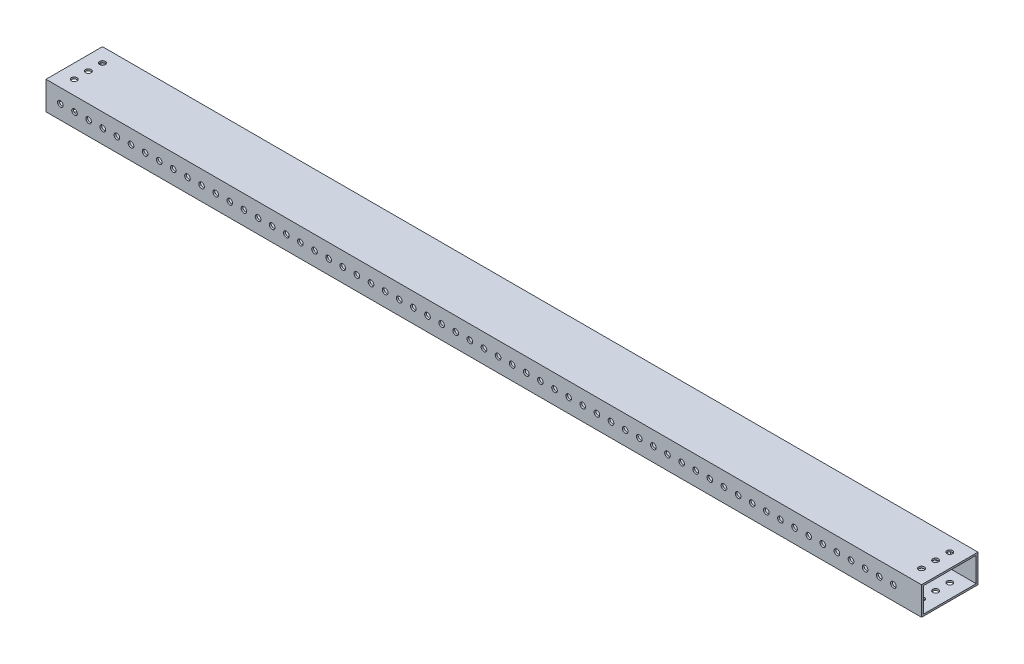
SolidWorks part; units mm, degrees
ref_plane "Front Plane" through (0, 0, 0) normal (0, 0, 1) x (1, 0, 0)
ref_plane "Top Plane" through (0, 0, 0) normal (0, 1, 0) x (1, 0, 0)
ref_plane "Right Plane" through (0, 0, 0) normal (1, 0, 0) x (0, 0, -1)
sketch "Sketch1" plane through (0, 0, 0) normal (0, 1, 0) x (1, 0, 0)
  line L1 (393.7901, 25.4) -> (-393.7901, 25.4)
  line L2 (393.7901, 25.4) -> (393.7901, -25.4)
  line L3 (393.7901, -25.4) -> (-393.7901, -25.4)
  line L4 (-393.7901, 25.4) -> (-393.7901, -25.4)
  line L5 (393.7901, 25.4) -> (-393.7901, -25.4) construction
  line L6 (393.7901, -25.4) -> (-393.7901, 25.4) construction
  point P0 (0, 0)
  dimension "D1" = 50.8
extrude "Boss-Extrude1" add sketch "Sketch1" along normal blind 25.4
sketch "Sketch2" plane through (-393.7901, 0, 0) normal (-1, 0, 0) x (0, 0, 1)
  line L1 (23.7937, 23.7836) -> (-23.7836, 23.7836)
  line L2 (23.7937, 23.7836) -> (23.7937, 1.6265)
  line L3 (23.7937, 1.6265) -> (-23.7836, 1.6265)
  line L4 (-23.7836, 23.7836) -> (-23.7836, 1.6265)
  line L6 (-25.4, 25.4) -> (-25.4, 0) construction
  line L7 (25.4, 25.4) -> (25.4, 0) construction
  dimension "D1" = 2.286
  dimension "D2" = 2.286
  dimension "D3" = 1.6164
  dimension "D4" = 1.6063
extrude "Cut-Extrude1" cut sketch "Sketch2" against normal through all
sketch "Sketch3" plane through (0, 0, 25.4) normal (0, 0, 1) x (1, 0, 0)
  line L0 (-1393.7901, 12.7) -> (48606.2099, 12.7) construction
  line L1 (-393.7901, 25.4) -> (-393.7901, 0) construction
  circle A1 centre (-380.8361, 12.7) radius 2.54
  circle A2 centre (-368.1361, 12.7) radius 2.54
  circle A3 centre (-355.4361, 12.7) radius 2.54
  circle A4 centre (-342.7361, 12.7) radius 2.54
  circle A5 centre (-330.0361, 12.7) radius 2.54
  circle A6 centre (-317.3361, 12.7) radius 2.54
  circle A7 centre (-304.6361, 12.7) radius 2.54
  circle A8 centre (-291.9361, 12.7) radius 2.54
  circle A9 centre (-279.2361, 12.7) radius 2.54
  circle A10 centre (-266.5361, 12.7) radius 2.54
  circle A11 centre (-253.8361, 12.7) radius 2.54
  circle A12 centre (-241.1361, 12.7) radius 2.54
  circle A13 centre (-228.4361, 12.7) radius 2.54
  circle A14 centre (-215.7361, 12.7) radius 2.54
  circle A15 centre (-203.0361, 12.7) radius 2.54
  circle A16 centre (-190.3361, 12.7) radius 2.54
  circle A17 centre (-177.6361, 12.7) radius 2.54
  circle A18 centre (-164.9361, 12.7) radius 2.54
  circle A19 centre (-152.2361, 12.7) radius 2.54
  circle A20 centre (-139.5361, 12.7) radius 2.54
  circle A21 centre (-126.8361, 12.7) radius 2.54
  circle A22 centre (-114.1361, 12.7) radius 2.54
  circle A23 centre (-101.4361, 12.7) radius 2.54
  circle A24 centre (-88.7361, 12.7) radius 2.54
  circle A25 centre (-76.0361, 12.7) radius 2.54
  circle A26 centre (-63.3361, 12.7) radius 2.54
  circle A27 centre (-50.6361, 12.7) radius 2.54
  circle A28 centre (-37.9361, 12.7) radius 2.54
  circle A29 centre (-25.2361, 12.7) radius 2.54
  circle A30 centre (-12.5361, 12.7) radius 2.54
  circle A31 centre (0.1639, 12.7) radius 2.54
  circle A32 centre (12.8639, 12.7) radius 2.54
  circle A33 centre (25.5639, 12.7) radius 2.54
  circle A34 centre (38.2639, 12.7) radius 2.54
  circle A35 centre (50.9639, 12.7) radius 2.54
  circle A36 centre (63.6639, 12.7) radius 2.54
  circle A37 centre (76.3639, 12.7) radius 2.54
  circle A38 centre (89.0639, 12.7) radius 2.54
  circle A39 centre (101.7639, 12.7) radius 2.54
  circle A40 centre (114.4639, 12.7) radius 2.54
  circle A41 centre (127.1639, 12.7) radius 2.54
  circle A42 centre (139.8639, 12.7) radius 2.54
  circle A43 centre (152.5639, 12.7) radius 2.54
  circle A44 centre (165.2639, 12.7) radius 2.54
  circle A45 centre (177.9639, 12.7) radius 2.54
  circle A46 centre (190.6639, 12.7) radius 2.54
  circle A47 centre (203.3639, 12.7) radius 2.54
  circle A48 centre (216.0639, 12.7) radius 2.54
  circle A49 centre (228.7639, 12.7) radius 2.54
  circle A50 centre (241.4639, 12.7) radius 2.54
  circle A51 centre (254.1639, 12.7) radius 2.54
  circle A52 centre (266.8639, 12.7) radius 2.54
  circle A53 centre (279.5639, 12.7) radius 2.54
  circle A54 centre (292.2639, 12.7) radius 2.54
  circle A55 centre (304.9639, 12.7) radius 2.54
  circle A56 centre (317.6639, 12.7) radius 2.54
  circle A57 centre (330.3639, 12.7) radius 2.54
  circle A58 centre (343.0639, 12.7) radius 2.54
  circle A59 centre (355.7639, 12.7) radius 2.54
  circle A60 centre (368.4639, 12.7) radius 2.54
  point P5 (-393.7901, 12.7)
  dimension "D1" = 5.08
  dimension "D2" = 12.954
  dimension "D4" = 12.7
  dimension "D3" = 60
extrude "Cut-Extrude2" cut sketch "Sketch3" against normal through all
sketch "Sketch4" plane through (0, 25.4, 0) normal (0, 1, 0) x (1, 0, 0)
  line L0 (-1393.7901, 0) -> (48606.2099, 0) construction
  line L1 (-393.7901, 25.4) -> (-393.7901, -25.4) construction
  line L2 (-1388.247, 12.7) -> (48611.753, 12.7) construction
  line L3 (-1379.4121, -12.7) -> (48620.5879, -12.7) construction
  line L4 (-393.7901, -25.4) -> (393.7901, -25.4) construction
  line L5 (0, 25.4) -> (0, -25.4) construction
  line L6 (393.7901, 25.4) -> (-393.7901, 25.4) construction
  circle A0 centre (-381.0901, 12.7) radius 2.54
  circle A2 centre (-381.0901, -12.7) radius 2.54
  circle A3 centre (-381.0901, 0) radius 2.54
  circle A4 centre (381.0901, 12.7) radius 2.54
  circle A5 centre (381.0901, 0) radius 2.54
  circle A6 centre (381.0901, -12.7) radius 2.54
  point P5 (-393.7901, 0)
  dimension "D1" = 5.08
  dimension "D5" = 12.7
  dimension "D6" = 5.08
  dimension "D2" = 12.7
  dimension "D3" = 12.7
  dimension "D4" = 12.7
extrude "Cut-Extrude3" cut sketch "Sketch4" against normal through all
